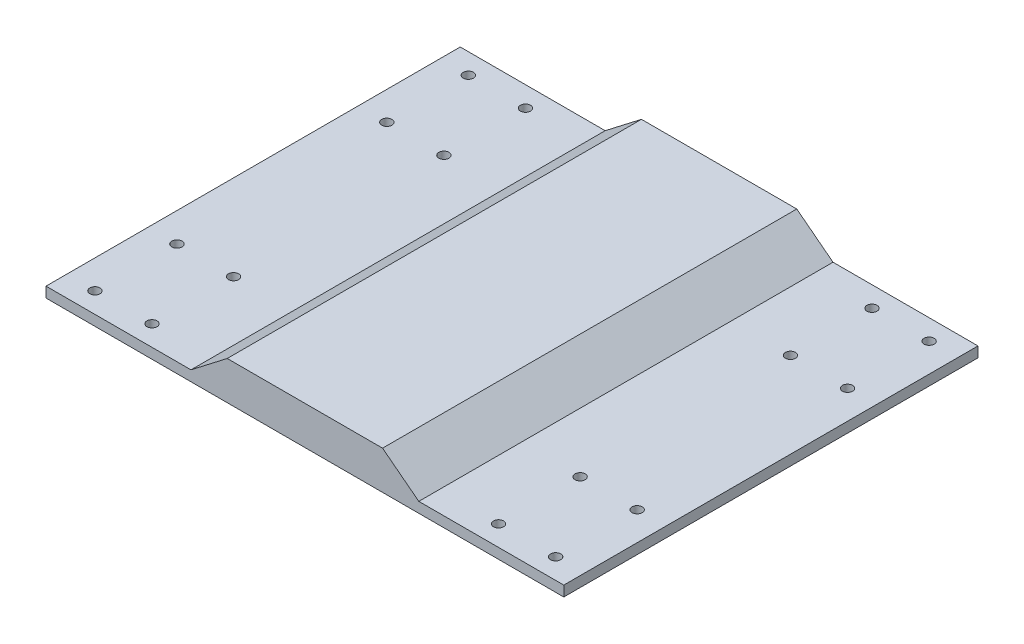
SolidWorks part; units mm, degrees
ref_plane "Front Plane" through (0, 0, 0) normal (0, 0, 1) x (1, 0, 0)
ref_plane "Top Plane" through (0, 0, 0) normal (0, 1, 0) x (1, 0, 0)
ref_plane "Right Plane" through (0, 0, 0) normal (1, 0, 0) x (0, 0, -1)
sketch "Sketch1" plane through (0, 0, 0) normal (0, 1, 0) x (1, 0, 0)
  line L1 (0, 0) -> (127, 0)
  line L2 (0, 0) -> (0, -101.6)
  line L3 (0, -101.6) -> (127, -101.6)
  line L4 (127, 0) -> (127, -101.6)
  dimension "D1" = 127
  dimension "D2" = 101.6
extrude "Boss-Extrude1" add sketch "Sketch1" along normal blind 2.54
hole_wizard "Tap Drill for M3x0.5 Tap1" positions "Sketch4" profile "Sketch5" hole size "M3x0.5" standard "ANSI Metric" end condition through all
sketch "Sketch4" plane through (0, 0, 0) normal (0, -1, 0) x (-1, 0, 0)
  line L0 (0, -96.6) -> (-127, -96.6) construction
  line L1 (0, 0) -> (0, -101.6) construction
  line L2 (-127, -101.6) -> (-127, 0) construction
  line L5 (0, -76.6) -> (-127, -76.6) construction
  line L8 (0, -25) -> (-127, -25) construction
  line L11 (0, -5) -> (-127, -5) construction
  line L14 (-21, -101.6) -> (-21, 0) construction
  line L15 (0, -101.6) -> (-127, -101.6) construction
  line L16 (-127, 0) -> (0, 0) construction
  line L19 (-7, 0) -> (-7, -101.6) construction
  line L22 (-120, -101.6) -> (-120, 0) construction
  line L25 (-106, 0) -> (-106, -101.6) construction
  point P130 (-120, -5)
  point P132 (-120, -25)
  point P134 (-106, -5)
  point P136 (-106, -25)
  point P138 (-120, -76.6)
  point P139 (-131.288, -76.6)
  point P141 (-120, -96.6)
  point P143 (-106, -96.6)
  point P145 (-21, -96.6)
  point P147 (-21, -76.6)
  point P149 (-7.112, -76.6)
  point P151 (-7, -96.6)
  point P153 (-21, -25)
  point P155 (-21, -5)
  point P157 (-7, -5)
  point P159 (-7, -25)
  point P160 (-106, -76.6)
  dimension "D1" = 7
  dimension "D2" = 5
  dimension "D3" = 7
  dimension "D4" = 5
  dimension "D5" = 14
  dimension "D6" = 20
  dimension "D7" = 20
  dimension "D8" = 14
sketch "Sketch5" plane through (106, 0, 76.6) normal (1, 0, 0) x (0, 0, -1)
  line L0 (0, 0) -> (0, 2.54)
  line L1 (0, 2.54) -> (1.25, 2.54)
  line L2 (1.25, 2.54) -> (1.25, 0)
  line L5 (1.25, 0) -> (0, 0)
  line L11 (0, -6.35) -> (0, 107.95) construction
  dimension "Thru Hole Dia." = 2.5
  dimension "Thru Hole Depth" = 2.54
sketch "Sketch6" plane through (0, 2.54, 0) normal (0, 1, 0) x (1, 0, 0)
  line L0 (127, 0) -> (0, 0) construction
  line L1 (35.56, 0) -> (91.44, 0)
  line L2 (35.56, 0) -> (35.56, -101.6)
  line L3 (35.56, -101.6) -> (91.44, -101.6)
  line L4 (91.44, 0) -> (91.44, -101.6)
  line L5 (0, -101.6) -> (127, -101.6) construction
  line L6 (0, -50.8) -> (127, -50.8) construction
  line L7 (0, 0) -> (0, -101.6) construction
  line L8 (127, -101.6) -> (127, 0) construction
  line L9 (63.5, 0) -> (63.5, -101.6) construction
  point P16 (63.5, -50.8)
  dimension "D1" = 55.88
ref_plane "Plane1" through (0, 9.398, 0) normal (0, 1, 0) x (1, 0, 0)
sketch "Sketch7" plane through (0, 9.398, 0) normal (0, 1, 0) x (1, 0, 0)
  line L0 (35.56, 0) -> (91.44, 0) construction
  line L1 (82.55, 0) -> (44.45, 0)
  line L2 (82.55, 0) -> (82.55, -101.6)
  line L3 (82.55, -101.6) -> (44.45, -101.6)
  line L4 (44.45, 0) -> (44.45, -101.6)
  line L5 (35.56, -101.6) -> (91.44, -101.6) construction
  line L6 (82.55, -50.8) -> (44.45, -50.8) construction
  line L7 (0, -50.8) -> (127, -50.8) construction
  line L8 (35.56, -50.8) -> (91.44, -50.8) construction
  line L9 (35.56, 0) -> (35.56, -101.6) construction
  line L10 (91.44, 0) -> (91.44, -101.6) construction
  point P10 (63.5, -50.8)
  point P19 (63.5, -50.8)
  dimension "D1" = 38.1
loft "Loft1" add profiles "Sketch7", "Sketch6"
